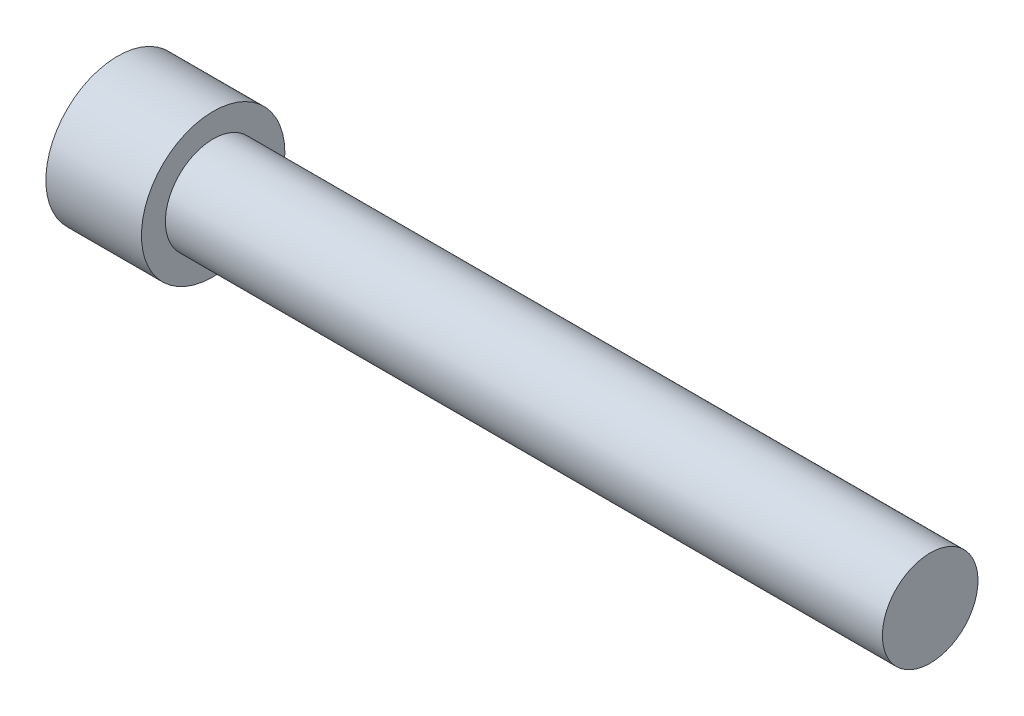
SolidWorks part; units mm, degrees
ref_plane "前视基准面" through (0, 0, 0) normal (0, 0, 1) x (1, 0, 0)
ref_plane "上视基准面" through (0, 0, 0) normal (0, 1, 0) x (1, 0, 0)
ref_plane "右视基准面" through (0, 0, 0) normal (1, 0, 0) x (0, 0, -1)
sketch "草图1" plane through (0, 0, 0) normal (1, 0, 0) x (0, 0, -1)
  circle A0 centre (0, 0) radius 3
  dimension "D1" = 6
extrude "凸台-拉伸1" add sketch "草图1" along normal blind 4
sketch "草图2" plane through (4, 0, 0) normal (1, 0, 0) x (0, 0, -1)
  circle A0 centre (0, 0) radius 2
  dimension "D1" = 4
extrude "凸台-拉伸2" add sketch "草图2" along normal blind 30
